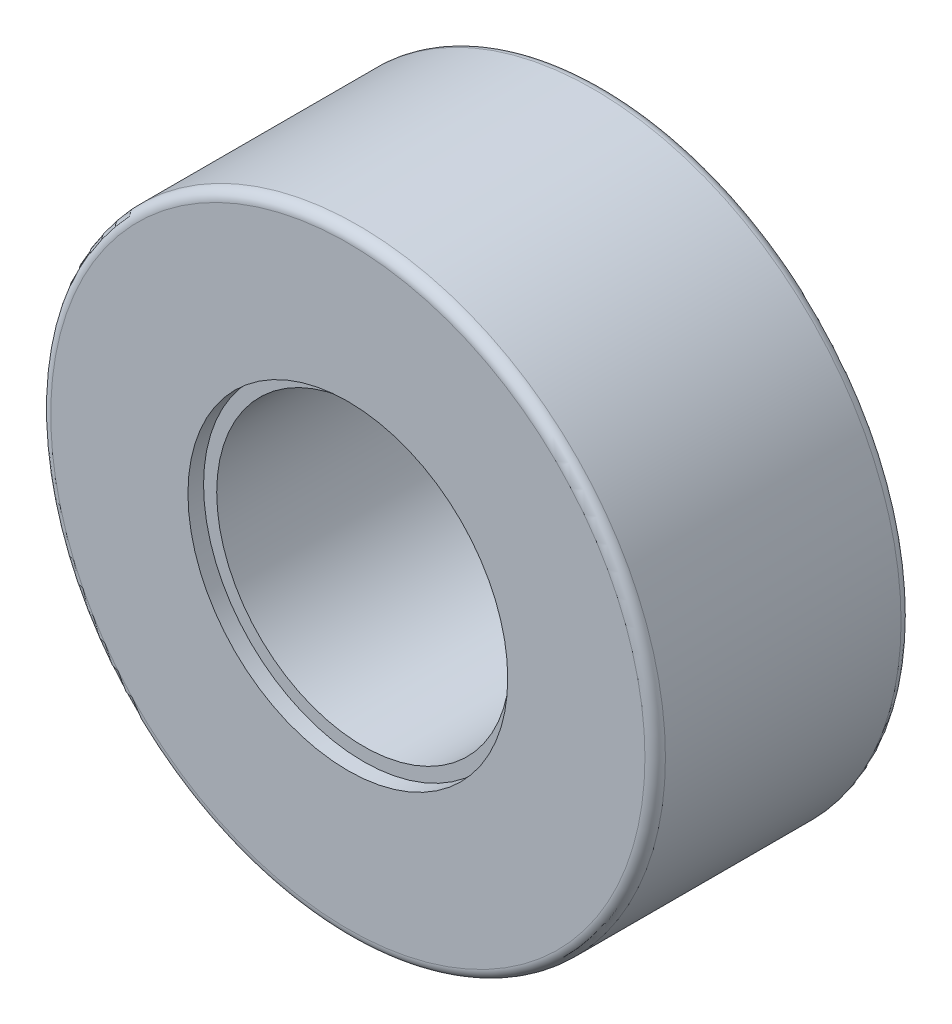
SolidWorks part; units mm, degrees
material "PETG"
ref_plane "Front Plane" through (0, 0, 0) normal (0, 0, 1) x (1, 0, 0)
ref_plane "Top Plane" through (0, 0, 0) normal (0, 1, 0) x (1, 0, 0)
ref_plane "Right Plane" through (0, 0, 0) normal (1, 0, 0) x (0, 0, -1)
sketch "Sketch1" plane through (0, 0, 0) normal (0, 0, 1) x (1, 0, 0)
  circle A0 centre (0, 0) radius 14.325
  circle A1 centre (0, 0) radius 30
  dimension "D1" = 60
  dimension "D2" = 28.65
extrude "Boss-Extrude1" add sketch "Sketch1" along normal mid plane 25
sketch "Sketch3" plane through (0, 0, 12.5) normal (0, 0, 1) x (1, 0, 0)
  circle A0 centre (0, 0) radius 15.6075
  dimension "D1" = 31.215
extrude "Cut-Extrude1" cut sketch "Sketch3" against normal blind 1.524
mirror "Mirror1" about plane through (0, 0, 0) normal (0, 0, 1) of "Cut-Extrude1"
fillet "Fillet1" radius 1 2 edges at (30, 0, -12.5) (30, 0, 12.5)
equation "\"tol_dia_id_intfc\" = 0.0500mm ' For hole diameters - Interference fit"
equation "\"tol_dia_id_slip\"  = 0.0750mm ' For hole diameters - Slip fit"
equation "\"tol_dia_id_clear\" = 0.1000mm ' For hole diameters - Clearance fit"
equation "\"tol_dia_od_intfc\" = 0.0500mm ' For shaft diameters - Interference fit"
equation "\"tol_dia_od_slip\"  = 0.0750mm ' For shaft diameters - Slip fit"
equation "\"tol_dia_od_clear\" = 0.1000mm ' For shaft diameters - Clearance fit"
equation "\"tol_general_intfc\"= 0.0250mm ' For general parts (Horiz) - Interference fit"
equation "\"tol_general_slip\" = 0.0375mm ' For general parts (Horiz) - Slip fit"
equation "\"tol_general_clear\"= 0.0500mm ' For general parts (Horiz) - Clearance fit"
equation "\"tol_layer_intfc\"  = 0.0250mm ' For all parts (Vert) - Interference fit"
equation "\"tol_layer_slip\"   = 0.0375mm ' For all parts (Vert) - Slip fit"
equation "\"tol_layer_clear\"  = 0.0500mm ' For all parts (Vert) - Clearance fit"
equation "\"tol_corner_rad\"   = 0.100mm ' For corners that fit into other parts"
equation "\"D2@Sketch1\"=1.125in + \"tol_dia_id_slip\""
equation "\"D1@Sketch3\"=1.225in + \"tol_dia_id_clear\""
